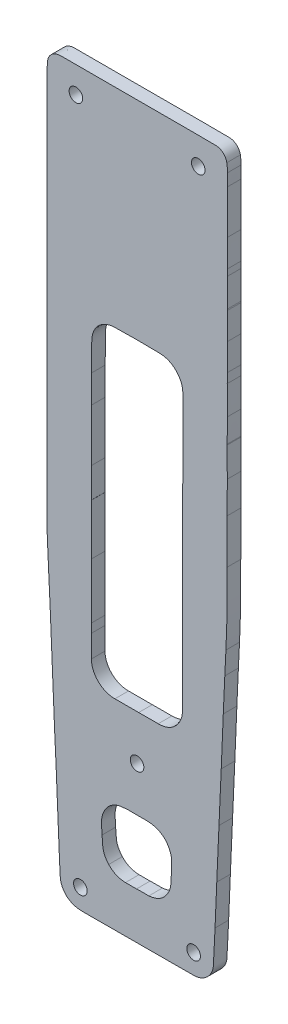
SolidWorks part; units mm, degrees
ref_plane "Front Plane" through (0, 0, 0) normal (0, 0, 1) x (1, 0, 0)
ref_plane "Top Plane" through (0, 0, 0) normal (0, 1, 0) x (1, 0, 0)
ref_plane "Right Plane" through (0, 0, 0) normal (1, 0, 0) x (0, 0, -1)
sketch "Model" plane through (0, 0, 0) normal (0, 0, 1) x (1, 0, 0)
  line L0 (141.7988, 114.6056) -> (166.7988, 114.6417) construction
  line L1 (140.8112, 265.5226) -> (167.8107, 265.3547) construction
  circle A0 centre (141.7988, 114.6056) radius 1.5
  circle A1 centre (166.7988, 114.6417) radius 1.5
  circle A2 centre (154.3108, 144.4893) radius 1.5
  circle A3 centre (140.8112, 265.5226) radius 1.5
  circle A4 centre (167.8107, 265.3547) radius 1.5
  spline S4 degree 3 poles (173.9199, 175.9786) (174.0098, 178.0904) (174.1211, 180.2026) (174.1462, 182.3156) (174.1843, 185.5284) (174.1561, 188.7419) (174.1561, 191.9552) knots 66 66 66 66 67 67 67 68 68 68 68
  spline S5 degree 3 poles (173.6655, 170.9124) (173.7446, 172.6014) (173.848, 174.2893) (173.9199, 175.9786) knots 65 65 65 65 66 66 66 66
  spline S6 degree 3 poles (173.3333, 163.4801) (173.4377, 165.9578) (173.5494, 168.4352) (173.6655, 170.9124) knots 64 64 64 64 65 65 65 65
  spline S7 degree 3 poles (172.8817, 152.7527) (172.9579, 154.4418) (173.0446, 156.1305) (173.1152, 157.8198) (173.194, 159.7063) (173.2538, 161.5937) (173.3333, 163.4801) knots 62 62 62 62 63 63 63 64 64 64 64
  spline S8 degree 3 poles (172.3862, 141.6873) (172.5506, 145.3758) (172.7153, 149.0643) (172.8817, 152.7527) knots 61 61 61 61 62 62 62 62
  spline S9 degree 3 poles (171.8957, 130.6212) (172.0558, 134.3101) (172.2218, 137.9986) (172.3862, 141.6873) knots 60 60 60 60 61 61 61 61
  spline S10 degree 3 poles (171.5164, 121.6673) (171.653, 124.6515) (171.7661, 127.6367) (171.8957, 130.6212) knots 59 59 59 59 60 60 60 60
  spline S11 degree 3 poles (166.7574, 110.2558) (169.0336, 110.2254) (170.5742, 111.9595) (170.9997, 113.4085) (171.0627, 113.6229) (171.1164, 113.8467) (171.1282, 114.0687) (171.2637, 116.6012) (171.4005, 119.1338) (171.5164, 121.6673) knots 56 56 56 56 57 57 57 58 58 58 59 59 59 59
  spline S12 degree 3 poles (142.6409, 110.1901) (148.0565, 110.199) (153.4722, 110.2157) (158.8878, 110.2329) (161.5111, 110.2412) (164.1348, 110.2909) (166.7574, 110.2558) knots 54 54 54 54 55 55 55 56 56 56 56
  spline S13 degree 3 poles (141.2095, 110.2826) (141.6817, 110.2157) (142.1636, 110.1893) (142.6409, 110.1901) knots 53 53 53 53 54 54 54 54
  spline S14 degree 3 poles (137.3627, 114.3523) (137.5387, 112.1621) (139.0313, 110.5913) (141.2095, 110.2826) knots 52 52 52 52 53 53 53 53
  spline S15 degree 3 poles (137.1861, 117.7294) (137.2378, 116.6033) (137.2725, 115.4755) (137.3627, 114.3523) knots 51 51 51 51 52 52 52 52
  spline S16 degree 3 poles (136.4535, 134.8761) (136.559, 132.4546) (136.6368, 130.0318) (136.7406, 127.6102) (136.8819, 124.3163) (137.0348, 121.0229) (137.1861, 117.7294) knots 49 49 49 49 50 50 50 51 51 51 51
  spline S17 degree 3 poles (136.1401, 141.2934) (136.2407, 139.1541) (136.3603, 137.0157) (136.4535, 134.8761) knots 48 48 48 48 49 49 49 49
  spline S18 degree 3 poles (135.1251, 164.9433) (135.2057, 163.1132) (135.2597, 161.282) (135.3365, 159.4518) (135.4782, 156.0731) (135.626, 152.6946) (135.7753, 149.3162) (135.8935, 146.6418) (136.0144, 143.9675) (136.1401, 141.2934) knots 45 45 45 45 46 46 46 47 47 47 48 48 48 48
  spline S19 degree 3 poles (134.8424, 170.684) (134.9362, 168.7704) (135.0408, 166.8573) (135.1251, 164.9433) knots 44 44 44 44 45 45 45 45
  spline S20 degree 3 poles (134.6254, 175.3278) (134.6405, 174.9899) (134.654, 174.6519) (134.6712, 174.3142) (134.7157, 173.442) (134.7636, 172.57) (134.8066, 171.6978) (134.8232, 171.3601) (134.8258, 171.0217) (134.8424, 170.684) knots 41 41 41 41 42 42 42 43 43 43 44 44 44 44
  spline S21 degree 3 poles (134.4924, 178.366) (134.5279, 177.3529) (134.5803, 176.3405) (134.6254, 175.3278) knots 40 40 40 40 41 41 41 41
  spline S22 degree 3 poles (134.3973, 188.1695) (134.3988, 185.9158) (134.4002, 183.6621) (134.4157, 181.4085) (134.4228, 180.3942) (134.4569, 179.3798) (134.4924, 178.366) knots 38 38 38 38 39 39 39 40 40 40 40
  spline S23 degree 3 poles (134.3975, 199.8379) (134.3945, 195.9484) (134.3948, 192.059) (134.3973, 188.1695) knots 37 37 37 37 38 38 38 38
  spline S24 degree 3 poles (134.4161, 216.3266) (134.4131, 212.8315) (134.4179, 209.3365) (134.415, 205.8415) (134.4133, 203.8403) (134.399, 201.8391) (134.3975, 199.8379) knots 35 35 35 35 36 36 36 37 37 37 37
  spline S25 degree 3 poles (134.4328, 227.1501) (134.4314, 223.5423) (134.4191, 219.9344) (134.4161, 216.3266) knots 34 34 34 34 35 35 35 35
  spline S26 degree 3 poles (134.45, 245.836) (134.4496, 244.1451) (134.4289, 242.4543) (134.4284, 240.7635) (134.427, 236.2257) (134.4345, 231.6879) (134.4328, 227.1501) knots 32 32 32 32 33 33 33 34 34 34 34
  spline S27 degree 3 poles (134.4422, 256.1499) (134.4384, 252.7119) (134.4508, 249.2739) (134.45, 245.836) knots 31 31 31 31 32 32 32 32
  spline S28 degree 3 poles (134.4782, 262.9986) (134.469, 260.7157) (134.4448, 258.4328) (134.4422, 256.1499) knots 30 30 30 30 31 31 31 31
  spline S29 degree 3 poles (134.5876, 268.9936) (134.5397, 268.6035) (134.491, 268.2105) (134.488, 267.8184) (134.4755, 266.2119) (134.4846, 264.6052) (134.4782, 262.9986) knots 28 28 28 28 29 29 29 30 30 30 30
  spline S30 degree 3 poles (174.1124, 269.2035) (173.9378, 270.3022) (172.9786, 271.2184) (171.7685, 271.2843) (171.487, 271.2997) (171.2049, 271.3119) (170.9231, 271.3125) (168.2719, 271.3179) (165.6207, 271.3207) (162.9694, 271.324) (160.9668, 271.3265) (158.9641, 271.332) (156.9615, 271.3302) (154.6203, 271.3282) (152.2792, 271.316) (149.9381, 271.3147) (145.8762, 271.3122) (141.8143, 271.3152) (137.7524, 271.314) (137.5269, 271.314) (137.3003, 271.3092) (137.0763, 271.2864) (135.9779, 271.1747) (134.7463, 270.2852) (134.5876, 268.9936) knots 20 20 20 20 21 21 21 22 22 22 23 23 23 24 24 24 25 25 25 26 26 26 27 27 27 28 28 28 28
  spline S31 degree 3 poles (174.2664, 267.3526) (174.2541, 267.9707) (174.2094, 268.5934) (174.1124, 269.2035) knots 19 19 19 19 20 20 20 20
  spline S32 degree 3 poles (174.2434, 264.6479) (174.2451, 265.5495) (174.2844, 266.4516) (174.2664, 267.3526) knots 18 18 18 18 19 19 19 19
  spline S33 degree 3 poles (174.2519, 255.0097) (174.2518, 257.659) (174.2709, 260.3082) (174.2759, 262.9575) (174.277, 263.521) (174.2424, 264.0845) (174.2434, 264.6479) knots 16 16 16 16 17 17 17 18 18 18 18
  spline S34 degree 3 poles (174.2837, 249.0084) (174.2758, 251.0089) (174.252, 253.0093) (174.2519, 255.0097) knots 15 15 15 15 16 16 16 16
  spline S35 degree 3 poles (174.256, 247.5719) (174.2666, 248.0507) (174.2855, 248.5296) (174.2837, 249.0084) knots 14 14 14 14 15 15 15 15
  spline S36 degree 3 poles (174.2605, 241.3188) (174.2534, 243.3188) (174.2472, 245.3187) (174.2419, 247.3187) (174.2417, 247.403) (174.2542, 247.4874) (174.256, 247.5719) knots 12 12 12 12 13 13 13 14 14 14 14
  spline S37 degree 3 poles (174.2749, 241.0656) (174.2755, 241.15) (174.2607, 241.2344) (174.2605, 241.3188) knots 11 11 11 11 12 12 12 12
  spline S38 degree 3 poles (174.2207, 235.0662) (174.2204, 235.1789) (174.2305, 235.2916) (174.2314, 235.4043) (174.2466, 237.2914) (174.2613, 239.1785) (174.2749, 241.0656) knots 9 9 9 9 10 10 10 11 11 11 11
  spline S39 degree 3 poles (174.2384, 229.1512) (174.237, 231.1229) (174.2267, 233.0945) (174.2207, 235.0662) knots 8 8 8 8 9 9 9 9
  spline S40 degree 3 poles (174.2089, 227.0384) (174.2069, 227.7426) (174.2388, 228.4469) (174.2384, 229.1512) knots 7 7 7 7 8 8 8 8
  spline S41 degree 3 poles (174.2394, 220.6987) (174.2404, 222.812) (174.215, 224.9252) (174.2089, 227.0384) knots 6 6 6 6 7 7 7 7
  spline S42 degree 3 poles (174.1952, 215.4588) (174.211, 217.2054) (174.2386, 218.9521) (174.2394, 220.6987) knots 5 5 5 5 6 6 6 6
  spline S43 degree 3 poles (174.1928, 215.2897) (174.1926, 215.346) (174.1947, 215.4024) (174.1952, 215.4588) knots 4 4 4 4 5 5 5 5
  spline S44 degree 3 poles (174.2146, 208.7808) (174.2141, 210.9504) (174.2005, 213.12) (174.1928, 215.2897) knots 3 3 3 3 4 4 4 4
  spline S45 degree 3 poles (174.1977, 201.7635) (174.2, 204.1026) (174.2151, 206.4417) (174.2146, 208.7808) knots 2 2 2 2 3 3 3 3
  spline S46 degree 3 poles (174.1969, 191.9551) (174.1969, 195.2246) (174.1946, 198.4941) (174.1977, 201.7635) knots 1 1 1 1 2 2 2 2
  spline S47 degree 3 poles (174.1561, 191.9552) (174.1697, 191.9551) (174.1833, 191.9551) (174.1969, 191.9551) knots 0 0 0 0 1 1 1 1
  spline S48 degree 3 poles (174.1969, 191.9551) (174.1833, 191.9551) (174.1697, 191.9551) (174.1561, 191.9552) knots 67 67 67 67 68 68 68 68
  spline S49 degree 3 poles (174.1977, 201.7635) (174.1946, 198.4941) (174.1969, 195.2246) (174.1969, 191.9551) knots 66 66 66 66 67 67 67 67
  spline S50 degree 3 poles (174.2146, 208.7808) (174.2151, 206.4417) (174.2, 204.1026) (174.1977, 201.7635) knots 65 65 65 65 66 66 66 66
  spline S51 degree 3 poles (174.1928, 215.2897) (174.2005, 213.12) (174.2141, 210.9504) (174.2146, 208.7808) knots 64 64 64 64 65 65 65 65
  spline S52 degree 3 poles (174.1952, 215.4588) (174.1947, 215.4024) (174.1926, 215.346) (174.1928, 215.2897) knots 63 63 63 63 64 64 64 64
  spline S53 degree 3 poles (174.2394, 220.6987) (174.2386, 218.9521) (174.211, 217.2054) (174.1952, 215.4588) knots 62 62 62 62 63 63 63 63
  spline S54 degree 3 poles (174.2089, 227.0384) (174.215, 224.9252) (174.2404, 222.812) (174.2394, 220.6987) knots 61 61 61 61 62 62 62 62
  spline S55 degree 3 poles (174.2384, 229.1512) (174.2388, 228.4469) (174.2069, 227.7426) (174.2089, 227.0384) knots 60 60 60 60 61 61 61 61
  spline S56 degree 3 poles (174.2207, 235.0662) (174.2267, 233.0945) (174.237, 231.1229) (174.2384, 229.1512) knots 59 59 59 59 60 60 60 60
  spline S57 degree 3 poles (174.2749, 241.0656) (174.2613, 239.1785) (174.2466, 237.2914) (174.2314, 235.4043) (174.2305, 235.2916) (174.2204, 235.1789) (174.2207, 235.0662) knots 57 57 57 57 58 58 58 59 59 59 59
  spline S58 degree 3 poles (174.2605, 241.3188) (174.2607, 241.2344) (174.2755, 241.15) (174.2749, 241.0656) knots 56 56 56 56 57 57 57 57
  spline S59 degree 3 poles (174.256, 247.5719) (174.2542, 247.4874) (174.2417, 247.403) (174.2419, 247.3187) (174.2472, 245.3187) (174.2534, 243.3188) (174.2605, 241.3188) knots 54 54 54 54 55 55 55 56 56 56 56
  spline S60 degree 3 poles (174.2837, 249.0084) (174.2855, 248.5296) (174.2666, 248.0507) (174.256, 247.5719) knots 53 53 53 53 54 54 54 54
  spline S61 degree 3 poles (174.2519, 255.0097) (174.252, 253.0093) (174.2758, 251.0089) (174.2837, 249.0084) knots 52 52 52 52 53 53 53 53
  spline S62 degree 3 poles (174.2434, 264.6479) (174.2424, 264.0845) (174.277, 263.521) (174.2759, 262.9575) (174.2709, 260.3082) (174.2518, 257.659) (174.2519, 255.0097) knots 50 50 50 50 51 51 51 52 52 52 52
  spline S63 degree 3 poles (174.2664, 267.3526) (174.2844, 266.4516) (174.2451, 265.5495) (174.2434, 264.6479) knots 49 49 49 49 50 50 50 50
  spline S64 degree 3 poles (174.1124, 269.2035) (174.2094, 268.5934) (174.2541, 267.9707) (174.2664, 267.3526) knots 48 48 48 48 49 49 49 49
  spline S65 degree 3 poles (134.5876, 268.9936) (134.7463, 270.2852) (135.9779, 271.1747) (137.0763, 271.2864) (137.3003, 271.3092) (137.5269, 271.314) (137.7524, 271.314) (141.8143, 271.3152) (145.8762, 271.3122) (149.9381, 271.3147) (152.2792, 271.316) (154.6203, 271.3282) (156.9615, 271.3302) (158.9641, 271.332) (160.9668, 271.3265) (162.9694, 271.324) (165.6207, 271.3207) (168.2719, 271.3179) (170.9231, 271.3125) (171.2049, 271.3119) (171.487, 271.2997) (171.7685, 271.2843) (172.9786, 271.2184) (173.9378, 270.3022) (174.1124, 269.2035) knots 40 40 40 40 41 41 41 42 42 42 43 43 43 44 44 44 45 45 45 46 46 46 47 47 47 48 48 48 48
  spline S66 degree 3 poles (134.4782, 262.9986) (134.4846, 264.6052) (134.4755, 266.2119) (134.488, 267.8184) (134.491, 268.2105) (134.5397, 268.6035) (134.5876, 268.9936) knots 38 38 38 38 39 39 39 40 40 40 40
  spline S67 degree 3 poles (134.4422, 256.1499) (134.4448, 258.4328) (134.469, 260.7157) (134.4782, 262.9986) knots 37 37 37 37 38 38 38 38
  spline S68 degree 3 poles (134.45, 245.836) (134.4508, 249.2739) (134.4384, 252.7119) (134.4422, 256.1499) knots 36 36 36 36 37 37 37 37
  spline S69 degree 3 poles (134.4328, 227.1501) (134.4345, 231.6879) (134.427, 236.2257) (134.4284, 240.7635) (134.4289, 242.4543) (134.4496, 244.1451) (134.45, 245.836) knots 34 34 34 34 35 35 35 36 36 36 36
  spline S70 degree 3 poles (134.4161, 216.3266) (134.4191, 219.9344) (134.4314, 223.5423) (134.4328, 227.1501) knots 33 33 33 33 34 34 34 34
  spline S71 degree 3 poles (134.3975, 199.8379) (134.399, 201.8391) (134.4133, 203.8403) (134.415, 205.8415) (134.4179, 209.3365) (134.4131, 212.8315) (134.4161, 216.3266) knots 31 31 31 31 32 32 32 33 33 33 33
  spline S72 degree 3 poles (134.3973, 188.1695) (134.3948, 192.059) (134.3945, 195.9484) (134.3975, 199.8379) knots 30 30 30 30 31 31 31 31
  spline S73 degree 3 poles (134.4924, 178.366) (134.4569, 179.3798) (134.4228, 180.3942) (134.4157, 181.4085) (134.4002, 183.6621) (134.3988, 185.9158) (134.3973, 188.1695) knots 28 28 28 28 29 29 29 30 30 30 30
  spline S74 degree 3 poles (134.6254, 175.3278) (134.5803, 176.3405) (134.5279, 177.3529) (134.4924, 178.366) knots 27 27 27 27 28 28 28 28
  spline S75 degree 3 poles (134.8424, 170.684) (134.8258, 171.0217) (134.8232, 171.3601) (134.8066, 171.6978) (134.7636, 172.57) (134.7157, 173.442) (134.6712, 174.3142) (134.654, 174.6519) (134.6405, 174.9899) (134.6254, 175.3278) knots 24 24 24 24 25 25 25 26 26 26 27 27 27 27
  spline S76 degree 3 poles (135.1251, 164.9433) (135.0408, 166.8573) (134.9362, 168.7704) (134.8424, 170.684) knots 23 23 23 23 24 24 24 24
  spline S77 degree 3 poles (136.1401, 141.2934) (136.0144, 143.9675) (135.8935, 146.6418) (135.7753, 149.3162) (135.626, 152.6946) (135.4782, 156.0731) (135.3365, 159.4518) (135.2597, 161.282) (135.2057, 163.1132) (135.1251, 164.9433) knots 20 20 20 20 21 21 21 22 22 22 23 23 23 23
  spline S78 degree 3 poles (136.4535, 134.8761) (136.3603, 137.0157) (136.2407, 139.1541) (136.1401, 141.2934) knots 19 19 19 19 20 20 20 20
  spline S79 degree 3 poles (137.1861, 117.7294) (137.0348, 121.0229) (136.8819, 124.3163) (136.7406, 127.6102) (136.6368, 130.0318) (136.559, 132.4546) (136.4535, 134.8761) knots 17 17 17 17 18 18 18 19 19 19 19
  spline S80 degree 3 poles (137.3627, 114.3523) (137.2725, 115.4755) (137.2378, 116.6033) (137.1861, 117.7294) knots 16 16 16 16 17 17 17 17
  spline S81 degree 3 poles (141.2095, 110.2826) (139.0313, 110.5913) (137.5387, 112.1621) (137.3627, 114.3523) knots 15 15 15 15 16 16 16 16
  spline S82 degree 3 poles (142.6409, 110.1901) (142.1636, 110.1893) (141.6817, 110.2157) (141.2095, 110.2826) knots 14 14 14 14 15 15 15 15
  spline S83 degree 3 poles (166.7574, 110.2558) (164.1348, 110.2909) (161.5111, 110.2412) (158.8878, 110.2329) (153.4722, 110.2157) (148.0565, 110.199) (142.6409, 110.1901) knots 12 12 12 12 13 13 13 14 14 14 14
  spline S84 degree 3 poles (171.5164, 121.6673) (171.4005, 119.1338) (171.2637, 116.6012) (171.1282, 114.0687) (171.1164, 113.8467) (171.0627, 113.6229) (170.9997, 113.4085) (170.5742, 111.9595) (169.0336, 110.2254) (166.7574, 110.2558) knots 9 9 9 9 10 10 10 11 11 11 12 12 12 12
  spline S85 degree 3 poles (171.8957, 130.6212) (171.7661, 127.6367) (171.653, 124.6515) (171.5164, 121.6673) knots 8 8 8 8 9 9 9 9
  spline S86 degree 3 poles (172.3862, 141.6873) (172.2218, 137.9986) (172.0558, 134.3101) (171.8957, 130.6212) knots 7 7 7 7 8 8 8 8
  spline S87 degree 3 poles (172.8817, 152.7527) (172.7153, 149.0643) (172.5506, 145.3758) (172.3862, 141.6873) knots 6 6 6 6 7 7 7 7
  spline S88 degree 3 poles (173.3333, 163.4801) (173.2538, 161.5937) (173.194, 159.7063) (173.1152, 157.8198) (173.0446, 156.1305) (172.9579, 154.4418) (172.8817, 152.7527) knots 4 4 4 4 5 5 5 6 6 6 6
  spline S89 degree 3 poles (173.6655, 170.9124) (173.5494, 168.4352) (173.4377, 165.9578) (173.3333, 163.4801) knots 3 3 3 3 4 4 4 4
  spline S90 degree 3 poles (173.9199, 175.9786) (173.848, 174.2893) (173.7446, 172.6014) (173.6655, 170.9124) knots 2 2 2 2 3 3 3 3
  spline S91 degree 3 poles (174.1561, 191.9552) (174.1561, 188.7419) (174.1843, 185.5284) (174.1462, 182.3156) (174.1211, 180.2026) (174.0098, 178.0904) (173.9199, 175.9786) knots 0 0 0 0 1 1 1 2 2 2 2
  spline S92 degree 3 poles (144.2161, 196.3716) (144.2109, 194.1737) (144.2148, 191.9757) (144.2148, 189.7778) knots 34 34 34 34 35 35 35 35
  spline S93 degree 3 poles (144.2548, 207.954) (144.2476, 205.8686) (144.2515, 203.7832) (144.2447, 201.6979) (144.239, 199.9225) (144.2202, 198.1471) (144.2161, 196.3716) knots 32 32 32 32 33 33 33 34 34 34 34
  spline S94 degree 3 poles (144.2876, 214.1255) (144.281, 212.0683) (144.2619, 210.0111) (144.2548, 207.954) knots 31 31 31 31 32 32 32 32
  spline S95 degree 3 poles (162.9135, 223.8566) (161.9623, 224.8252) (160.7993, 225.3269) (159.4357, 225.3701) (156.1079, 225.4755) (152.7803, 225.4668) (149.4527, 225.3707) (149.2836, 225.3658) (149.1144, 225.3558) (148.946, 225.3395) (146.6879, 225.1199) (144.9247, 223.5911) (144.4375, 221.3828) (144.3234, 220.8659) (144.3019, 220.3212) (144.2971, 219.7888) (144.2805, 217.9011) (144.2937, 216.0132) (144.2876, 214.1255) knots 25 25 25 25 26 26 26 27 27 27 28 28 28 29 29 29 30 30 30 31 31 31 31
  spline S96 degree 3 poles (164.4054, 220.3708) (164.3893, 221.7345) (163.8603, 222.8924) (162.9135, 223.8566) knots 24 24 24 24 25 25 25 25
  spline S97 degree 3 poles (164.3736, 182.9155) (164.3778, 184.9445) (164.3581, 186.9736) (164.3592, 189.0026) (164.3616, 193.3711) (164.3696, 197.7395) (164.3772, 202.108) (164.3859, 207.1247) (164.397, 212.1413) (164.4064, 217.158) (164.4084, 218.2289) (164.418, 219.3) (164.4054, 220.3708) knots 20 20 20 20 21 21 21 22 22 22 23 23 23 24 24 24 24
  spline S98 degree 3 poles (164.3443, 171.7592) (164.3452, 173.5902) (164.3287, 175.4212) (164.3337, 177.2522) (164.3388, 179.14) (164.3696, 181.0277) (164.3736, 182.9155) knots 18 18 18 18 19 19 19 20 20 20 20
  spline S99 degree 3 poles (164.3119, 169.5619) (164.3184, 170.2944) (164.344, 171.0268) (164.3443, 171.7592) knots 17 17 17 17 18 18 18 18
  spline S100 degree 3 poles (164.3197, 168.125) (164.3198, 168.604) (164.3077, 169.083) (164.3119, 169.5619) knots 16 16 16 16 17 17 17 17
  spline S101 degree 3 poles (164.3134, 165.7581) (164.3142, 166.5471) (164.3196, 167.3361) (164.3197, 168.125) knots 15 15 15 15 16 16 16 16
  spline S102 degree 3 poles (164.3171, 164.0691) (164.3184, 164.6321) (164.3128, 165.1951) (164.3134, 165.7581) knots 14 14 14 14 15 15 15 15
  spline S103 degree 3 poles (162.4909, 155.6627) (163.7583, 156.8005) (164.4014, 158.2128) (164.3308, 159.9302) (164.3181, 160.2392) (164.3067, 160.5486) (164.3069, 160.8578) (164.3076, 161.9282) (164.3148, 162.9987) (164.3171, 164.0691) knots 11 11 11 11 12 12 12 13 13 13 14 14 14 14
  spline S104 degree 3 poles (158.9831, 154.4253) (160.2953, 154.4307) (161.4952, 154.7688) (162.4909, 155.6627) knots 10 10 10 10 11 11 11 11
  spline S105 degree 3 poles (154.6683, 154.4165) (156.1066, 154.4171) (157.5449, 154.4194) (158.9831, 154.4253) knots 9 9 9 9 10 10 10 10
  spline S106 degree 3 poles (149.4234, 154.4129) (151.1711, 154.4463) (152.9199, 154.4157) (154.6683, 154.4165) knots 8 8 8 8 9 9 9 9
  spline S107 degree 3 poles (144.2257, 159.4272) (144.2682, 156.4834) (146.7049, 154.361) (149.4234, 154.4129) knots 7 7 7 7 8 8 8 8
  spline S108 degree 3 poles (144.2253, 164.3302) (144.226, 162.6958) (144.2022, 161.0612) (144.2257, 159.4272) knots 6 6 6 6 7 7 7 7
  spline S109 degree 3 poles (144.2127, 166.2744) (144.2107, 165.6264) (144.2251, 164.9783) (144.2253, 164.3302) knots 5 5 5 5 6 6 6 6
  spline S110 degree 3 poles (144.224, 178.5326) (144.2242, 176.4474) (144.2388, 174.3621) (144.237, 172.2768) (144.2352, 170.276) (144.2187, 168.2752) (144.2127, 166.2744) knots 3 3 3 3 4 4 4 5 5 5 5
  spline S111 degree 3 poles (144.2334, 189.7777) (144.2334, 188.9041) (144.2342, 188.0305) (144.2333, 187.157) (144.2302, 184.2822) (144.2236, 181.4074) (144.224, 178.5326) knots 1 1 1 1 2 2 2 3 3 3 3
  spline S112 degree 3 poles (144.2148, 189.7778) (144.221, 189.7778) (144.2272, 189.7777) (144.2334, 189.7777) knots 0 0 0 0 1 1 1 1
  spline S113 degree 3 poles (151.7525, 120.4667) (152.5695, 120.4421) (153.3878, 120.4623) (154.2055, 120.4623) knots 15 15 15 15 16 16 16 16
  spline S114 degree 3 poles (148.0595, 122.0806) (149.0541, 121.0038) (150.3104, 120.5102) (151.7525, 120.4667) knots 14 14 14 14 15 15 15 15
  spline S115 degree 3 poles (146.5829, 126.9669) (146.6318, 126.2363) (146.6698, 125.5034) (146.7597, 124.7774) (146.8882, 123.7391) (147.3516, 122.8469) (148.0595, 122.0806) knots 12 12 12 12 13 13 13 14 14 14 14
  spline S116 degree 3 poles (150.8594, 134.527) (148.2112, 134.2062) (146.3305, 131.7314) (146.4671, 129.0756) (146.5032, 128.3726) (146.536, 127.6692) (146.5829, 126.9669) knots 10 10 10 10 11 11 11 12 12 12 12
  spline S117 degree 3 poles (156.2639, 134.6322) (154.9683, 134.6708) (153.6708, 134.6606) (152.3743, 134.6465) (151.8689, 134.6411) (151.3621, 134.5879) (150.8594, 134.527) knots 8 8 8 8 9 9 9 10 10 10 10
  spline S118 degree 3 poles (158.2692, 134.3884) (157.6325, 134.5788) (156.9358, 134.6121) (156.2639, 134.6322) knots 7 7 7 7 8 8 8 8
  spline S119 degree 3 poles (161.6989, 131.0581) (161.1354, 132.7666) (159.9695, 133.8798) (158.2692, 134.3884) knots 6 6 6 6 7 7 7 7
  spline S120 degree 3 poles (161.949, 129.1412) (161.9738, 129.7939) (161.9049, 130.4335) (161.6989, 131.0581) knots 5 5 5 5 6 6 6 6
  spline S121 degree 3 poles (161.8136, 125.7632) (161.8658, 126.8889) (161.9062, 128.0151) (161.949, 129.1412) knots 4 4 4 4 5 5 5 5
  spline S122 degree 3 poles (161.4426, 123.7798) (161.7129, 124.4132) (161.7823, 125.0862) (161.8136, 125.7632) knots 3 3 3 3 4 4 4 4
  spline S123 degree 3 poles (156.9112, 120.4965) (159.0749, 120.6656) (160.5893, 121.7801) (161.4426, 123.7798) knots 2 2 2 2 3 3 3 3
  spline S124 degree 3 poles (154.2056, 120.4849) (155.1078, 120.4849) (156.0145, 120.4265) (156.9112, 120.4965) knots 1 1 1 1 2 2 2 2
  spline S125 degree 3 poles (154.2055, 120.4623) (154.2056, 120.4698) (154.2056, 120.4774) (154.2056, 120.4849) knots 0 0 0 0 1 1 1 1
  spline S126 degree 3 poles (154.3801, 142.9909) (155.2009, 143.0138) (155.8331, 143.6864) (155.8106, 144.5128) knots 3 3 3 3 4 4 4 4 construction
  spline S127 degree 3 poles (152.6659, 144.4558) (152.6872, 143.6048) (153.4443, 142.9578) (154.3801, 142.9909) knots 2 2 2 2 3 3 3 3 construction
  spline S128 degree 3 poles (154.2237, 145.9868) (153.3377, 145.9686) (152.6579, 145.3005) (152.6659, 144.4558) knots 1 1 1 1 2 2 2 2 construction
  spline S129 degree 3 poles (155.8106, 144.5128) (155.7877, 145.355) (155.0812, 146.0112) (154.2237, 145.9868) knots 0 0 0 0 1 1 1 1 construction
  spline S130 degree 3 poles (140.3289, 264.1022) (140.9403, 263.8539) (141.5162, 263.9626) (141.9949, 264.3926) (142.4492, 264.8008) (142.608, 265.3451) (142.4563, 265.9435) (142.2981, 266.568) (141.836, 266.8641) (141.232, 266.9751) (141.1207, 266.9955) (141.0074, 267.005) (140.8869, 267.0206) knots 3 3 3 3 4 4 4 5 5 5 6 6 6 7 7 7 7 construction
  spline S131 degree 3 poles (139.3257, 265.7305) (139.2748, 265.0348) (139.6798, 264.3658) (140.3289, 264.1022) knots 2 2 2 2 3 3 3 3 construction
  spline S132 degree 3 poles (140.5586, 266.9642) (139.893, 266.8244) (139.3706, 266.2995) (139.3257, 265.7305) knots 1 1 1 1 2 2 2 2 construction
  spline S133 degree 3 poles (140.8869, 267.0206) (140.7814, 267.0029) (140.6678, 266.9921) (140.5586, 266.9642) knots 0 0 0 0 1 1 1 1 construction
  spline S134 degree 3 poles (141.2017, 115.9816) (140.9988, 115.8937) (140.8204, 115.7508) (140.6241, 115.6453) (140.2619, 115.4507) (140.1088, 115.1514) (140.146, 114.8272) knots 4 4 4 4 5 5 5 6 6 6 6 construction
  spline S135 degree 3 poles (143.0015, 115.502) (142.5793, 116.0341) (141.8033, 116.2488) (141.2017, 115.9816) knots 3 3 3 3 4 4 4 4 construction
  spline S136 degree 3 poles (142.9597, 113.6557) (143.4066, 114.2176) (143.4236, 114.97) (143.0015, 115.502) knots 2 2 2 2 3 3 3 3 construction
  spline S137 degree 3 poles (140.146, 114.8272) (140.1489, 114.024) (140.5267, 113.5392) (141.1466, 113.2316) (141.7565, 112.929) (142.538, 113.1238) (142.9597, 113.6557) knots 0 0 0 0 1 1 1 2 2 2 2 construction
  spline S138 degree 3 poles (165.1955, 114.5449) (165.2276, 113.7683) (165.9548, 113.1286) (166.7906, 113.1418) knots 3 3 3 3 4 4 4 4 construction
  spline S139 degree 3 poles (166.7771, 116.1416) (165.8956, 116.1537) (165.1648, 115.416) (165.1955, 114.5449) knots 2 2 2 2 3 3 3 3 construction
  spline S140 degree 3 poles (168.2978, 114.5886) (168.2935, 115.4667) (167.6418, 116.1323) (166.7771, 116.1416) knots 1 1 1 1 2 2 2 2 construction
  spline S141 degree 3 poles (166.7906, 113.1418) (167.6719, 113.1528) (168.3019, 113.7575) (168.2978, 114.5886) knots 0 0 0 0 1 1 1 1 construction
  spline S142 degree 3 poles (169.3087, 265.4315) (169.3446, 266.266) (168.7657, 266.8488) (167.8375, 266.8544) knots 4 4 4 4 5 5 5 5 construction
  spline S143 degree 3 poles (166.3107, 265.3517) (166.3719, 264.7011) (166.9812, 264.1317) (167.6844, 264.0678) (168.51, 263.9928) (169.2743, 264.6345) (169.3087, 265.4315) knots 2 2 2 2 3 3 3 4 4 4 4 construction
  spline S144 degree 3 poles (167.8375, 266.8544) (167.76, 266.8493) (167.6235, 266.849) (167.4895, 266.8302) (166.6994, 266.7195) (166.2367, 266.1369) (166.3107, 265.3517) knots 0 0 0 0 1 1 1 2 2 2 2 construction
  spline S145 degree 3 poles (144.2334, 189.7777) (144.2272, 189.7777) (144.221, 189.7778) (144.2148, 189.7778) knots 34 34 34 34 35 35 35 35
  spline S146 degree 3 poles (144.224, 178.5326) (144.2236, 181.4074) (144.2302, 184.2822) (144.2333, 187.157) (144.2342, 188.0305) (144.2334, 188.9041) (144.2334, 189.7777) knots 32 32 32 32 33 33 33 34 34 34 34
  spline S147 degree 3 poles (144.2127, 166.2744) (144.2187, 168.2752) (144.2352, 170.276) (144.237, 172.2768) (144.2388, 174.3621) (144.2242, 176.4474) (144.224, 178.5326) knots 30 30 30 30 31 31 31 32 32 32 32
  spline S148 degree 3 poles (144.2253, 164.3302) (144.2251, 164.9783) (144.2107, 165.6264) (144.2127, 166.2744) knots 29 29 29 29 30 30 30 30
  spline S149 degree 3 poles (144.2257, 159.4272) (144.2022, 161.0612) (144.226, 162.6958) (144.2253, 164.3302) knots 28 28 28 28 29 29 29 29
  spline S150 degree 3 poles (149.4234, 154.4129) (146.7049, 154.361) (144.2682, 156.4834) (144.2257, 159.4272) knots 27 27 27 27 28 28 28 28
  spline S151 degree 3 poles (154.6683, 154.4165) (152.9199, 154.4157) (151.1711, 154.4463) (149.4234, 154.4129) knots 26 26 26 26 27 27 27 27
  spline S152 degree 3 poles (158.9831, 154.4253) (157.5449, 154.4194) (156.1066, 154.4171) (154.6683, 154.4165) knots 25 25 25 25 26 26 26 26
  spline S153 degree 3 poles (162.4909, 155.6627) (161.4952, 154.7688) (160.2953, 154.4307) (158.9831, 154.4253) knots 24 24 24 24 25 25 25 25
  spline S154 degree 3 poles (164.3171, 164.0691) (164.3148, 162.9987) (164.3076, 161.9282) (164.3069, 160.8578) (164.3067, 160.5486) (164.3181, 160.2392) (164.3308, 159.9302) (164.4014, 158.2128) (163.7583, 156.8005) (162.4909, 155.6627) knots 21 21 21 21 22 22 22 23 23 23 24 24 24 24
  spline S155 degree 3 poles (164.3134, 165.7581) (164.3128, 165.1951) (164.3184, 164.6321) (164.3171, 164.0691) knots 20 20 20 20 21 21 21 21
  spline S156 degree 3 poles (164.3197, 168.125) (164.3196, 167.3361) (164.3142, 166.5471) (164.3134, 165.7581) knots 19 19 19 19 20 20 20 20
  spline S157 degree 3 poles (164.3119, 169.5619) (164.3077, 169.083) (164.3198, 168.604) (164.3197, 168.125) knots 18 18 18 18 19 19 19 19
  spline S158 degree 3 poles (164.3443, 171.7592) (164.344, 171.0268) (164.3184, 170.2944) (164.3119, 169.5619) knots 17 17 17 17 18 18 18 18
  spline S159 degree 3 poles (164.3736, 182.9155) (164.3696, 181.0277) (164.3388, 179.14) (164.3337, 177.2522) (164.3287, 175.4212) (164.3452, 173.5902) (164.3443, 171.7592) knots 15 15 15 15 16 16 16 17 17 17 17
  spline S160 degree 3 poles (164.4054, 220.3708) (164.418, 219.3) (164.4084, 218.2289) (164.4064, 217.158) (164.397, 212.1413) (164.3859, 207.1247) (164.3772, 202.108) (164.3696, 197.7395) (164.3616, 193.3711) (164.3592, 189.0026) (164.3581, 186.9736) (164.3778, 184.9445) (164.3736, 182.9155) knots 11 11 11 11 12 12 12 13 13 13 14 14 14 15 15 15 15
  spline S161 degree 3 poles (162.9135, 223.8566) (163.8603, 222.8924) (164.3893, 221.7345) (164.4054, 220.3708) knots 10 10 10 10 11 11 11 11
  spline S162 degree 3 poles (144.2876, 214.1255) (144.2937, 216.0132) (144.2805, 217.9011) (144.2971, 219.7888) (144.3019, 220.3212) (144.3234, 220.8659) (144.4375, 221.3828) (144.9247, 223.5911) (146.6879, 225.1199) (148.946, 225.3395) (149.1144, 225.3558) (149.2836, 225.3658) (149.4527, 225.3707) (152.7803, 225.4668) (156.1079, 225.4755) (159.4357, 225.3701) (160.7993, 225.3269) (161.9623, 224.8252) (162.9135, 223.8566) knots 4 4 4 4 5 5 5 6 6 6 7 7 7 8 8 8 9 9 9 10 10 10 10
  spline S163 degree 3 poles (144.2548, 207.954) (144.2619, 210.0111) (144.281, 212.0683) (144.2876, 214.1255) knots 3 3 3 3 4 4 4 4
  spline S164 degree 3 poles (144.2161, 196.3716) (144.2202, 198.1471) (144.239, 199.9225) (144.2447, 201.6979) (144.2515, 203.7832) (144.2476, 205.8686) (144.2548, 207.954) knots 1 1 1 1 2 2 2 3 3 3 3
  spline S165 degree 3 poles (144.2148, 189.7778) (144.2148, 191.9757) (144.2109, 194.1737) (144.2161, 196.3716) knots 0 0 0 0 1 1 1 1
  spline S166 degree 3 poles (154.2056, 120.4849) (154.2056, 120.4774) (154.2056, 120.4698) (154.2055, 120.4623) knots 15 15 15 15 16 16 16 16
  spline S167 degree 3 poles (156.9112, 120.4965) (156.0145, 120.4265) (155.1078, 120.4849) (154.2056, 120.4849) knots 14 14 14 14 15 15 15 15
  spline S168 degree 3 poles (161.4426, 123.7798) (160.5893, 121.7801) (159.0749, 120.6656) (156.9112, 120.4965) knots 13 13 13 13 14 14 14 14
  spline S169 degree 3 poles (161.8136, 125.7632) (161.7823, 125.0862) (161.7129, 124.4132) (161.4426, 123.7798) knots 12 12 12 12 13 13 13 13
  spline S170 degree 3 poles (161.949, 129.1412) (161.9062, 128.0151) (161.8658, 126.8889) (161.8136, 125.7632) knots 11 11 11 11 12 12 12 12
  spline S171 degree 3 poles (161.6989, 131.0581) (161.9049, 130.4335) (161.9738, 129.7939) (161.949, 129.1412) knots 10 10 10 10 11 11 11 11
  spline S172 degree 3 poles (158.2692, 134.3884) (159.9695, 133.8798) (161.1354, 132.7666) (161.6989, 131.0581) knots 9 9 9 9 10 10 10 10
  spline S173 degree 3 poles (156.2639, 134.6322) (156.9358, 134.6121) (157.6325, 134.5788) (158.2692, 134.3884) knots 8 8 8 8 9 9 9 9
  spline S174 degree 3 poles (150.8594, 134.527) (151.3621, 134.5879) (151.8689, 134.6411) (152.3743, 134.6465) (153.6708, 134.6606) (154.9683, 134.6708) (156.2639, 134.6322) knots 6 6 6 6 7 7 7 8 8 8 8
  spline S175 degree 3 poles (146.5829, 126.9669) (146.536, 127.6692) (146.5032, 128.3726) (146.4671, 129.0756) (146.3305, 131.7314) (148.2112, 134.2062) (150.8594, 134.527) knots 4 4 4 4 5 5 5 6 6 6 6
  spline S176 degree 3 poles (148.0595, 122.0806) (147.3516, 122.8469) (146.8882, 123.7391) (146.7597, 124.7774) (146.6698, 125.5034) (146.6318, 126.2363) (146.5829, 126.9669) knots 2 2 2 2 3 3 3 4 4 4 4
  spline S177 degree 3 poles (151.7525, 120.4667) (150.3104, 120.5102) (149.0541, 121.0038) (148.0595, 122.0806) knots 1 1 1 1 2 2 2 2
  spline S178 degree 3 poles (154.2055, 120.4623) (153.3878, 120.4623) (152.5695, 120.4421) (151.7525, 120.4667) knots 0 0 0 0 1 1 1 1
  spline S179 degree 3 poles (154.2237, 145.9868) (155.0812, 146.0112) (155.7877, 145.355) (155.8106, 144.5128) knots 3 3 3 3 4 4 4 4 construction
  spline S180 degree 3 poles (152.6659, 144.4558) (152.6579, 145.3005) (153.3377, 145.9686) (154.2237, 145.9868) knots 2 2 2 2 3 3 3 3 construction
  spline S181 degree 3 poles (154.3801, 142.9909) (153.4443, 142.9578) (152.6872, 143.6048) (152.6659, 144.4558) knots 1 1 1 1 2 2 2 2 construction
  spline S182 degree 3 poles (155.8106, 144.5128) (155.8331, 143.6864) (155.2009, 143.0138) (154.3801, 142.9909) knots 0 0 0 0 1 1 1 1 construction
  spline S183 degree 3 poles (140.5586, 266.9642) (140.6678, 266.9921) (140.7814, 267.0029) (140.8869, 267.0206) knots 6 6 6 6 7 7 7 7 construction
  spline S184 degree 3 poles (139.3257, 265.7305) (139.3706, 266.2995) (139.893, 266.8244) (140.5586, 266.9642) knots 5 5 5 5 6 6 6 6 construction
  spline S185 degree 3 poles (140.3289, 264.1022) (139.6798, 264.3658) (139.2748, 265.0348) (139.3257, 265.7305) knots 4 4 4 4 5 5 5 5 construction
  spline S186 degree 3 poles (140.8869, 267.0206) (141.0074, 267.005) (141.1207, 266.9955) (141.232, 266.9751) (141.836, 266.8641) (142.2981, 266.568) (142.4563, 265.9435) (142.608, 265.3451) (142.4492, 264.8008) (141.9949, 264.3926) (141.5162, 263.9626) (140.9403, 263.8539) (140.3289, 264.1022) knots 0 0 0 0 1 1 1 2 2 2 3 3 3 4 4 4 4 construction
  spline S187 degree 3 poles (142.9597, 113.6557) (142.538, 113.1238) (141.7565, 112.929) (141.1466, 113.2316) (140.5267, 113.5392) (140.1489, 114.024) (140.146, 114.8272) knots 4 4 4 4 5 5 5 6 6 6 6 construction
  spline S188 degree 3 poles (143.0015, 115.502) (143.4236, 114.97) (143.4066, 114.2176) (142.9597, 113.6557) knots 3 3 3 3 4 4 4 4 construction
  spline S189 degree 3 poles (141.2017, 115.9816) (141.8033, 116.2488) (142.5793, 116.0341) (143.0015, 115.502) knots 2 2 2 2 3 3 3 3 construction
  spline S190 degree 3 poles (140.146, 114.8272) (140.1088, 115.1514) (140.2619, 115.4507) (140.6241, 115.6453) (140.8204, 115.7508) (140.9988, 115.8937) (141.2017, 115.9816) knots 0 0 0 0 1 1 1 2 2 2 2 construction
  spline S191 degree 3 poles (168.2978, 114.5886) (168.3019, 113.7575) (167.6719, 113.1528) (166.7906, 113.1418) knots 3 3 3 3 4 4 4 4 construction
  spline S192 degree 3 poles (166.7771, 116.1416) (167.6418, 116.1323) (168.2935, 115.4667) (168.2978, 114.5886) knots 2 2 2 2 3 3 3 3 construction
  spline S193 degree 3 poles (165.1955, 114.5449) (165.1648, 115.416) (165.8956, 116.1537) (166.7771, 116.1416) knots 1 1 1 1 2 2 2 2 construction
  spline S194 degree 3 poles (166.7906, 113.1418) (165.9548, 113.1286) (165.2276, 113.7683) (165.1955, 114.5449) knots 0 0 0 0 1 1 1 1 construction
  spline S195 degree 3 poles (166.3107, 265.3517) (166.2367, 266.1369) (166.6994, 266.7195) (167.4895, 266.8302) (167.6235, 266.849) (167.76, 266.8493) (167.8375, 266.8544) knots 3 3 3 3 4 4 4 5 5 5 5 construction
  spline S196 degree 3 poles (169.3087, 265.4315) (169.2743, 264.6345) (168.51, 263.9928) (167.6844, 264.0678) (166.9812, 264.1317) (166.3719, 264.7011) (166.3107, 265.3517) knots 1 1 1 1 2 2 2 3 3 3 3 construction
  spline S197 degree 3 poles (167.8375, 266.8544) (168.7657, 266.8488) (169.3446, 266.266) (169.3087, 265.4315) knots 0 0 0 0 1 1 1 1 construction
extrude "Boss-Extrude1" add sketch "Model" along normal blind 3 contours S4 S47 S46 S45 S44 S43 S42 S41 S40 S39 S38 S37 S36 S35 S34 S33 S32 S31 S30 S29 S28 S27 S26 S25 S24 S23 S22 S21 S20 S19 S18 S17 S16 S15 S14 S13 S12 S11 S10 S9 S8 S7 S6 S5 S125 S113 S114 S115 S116 S117
